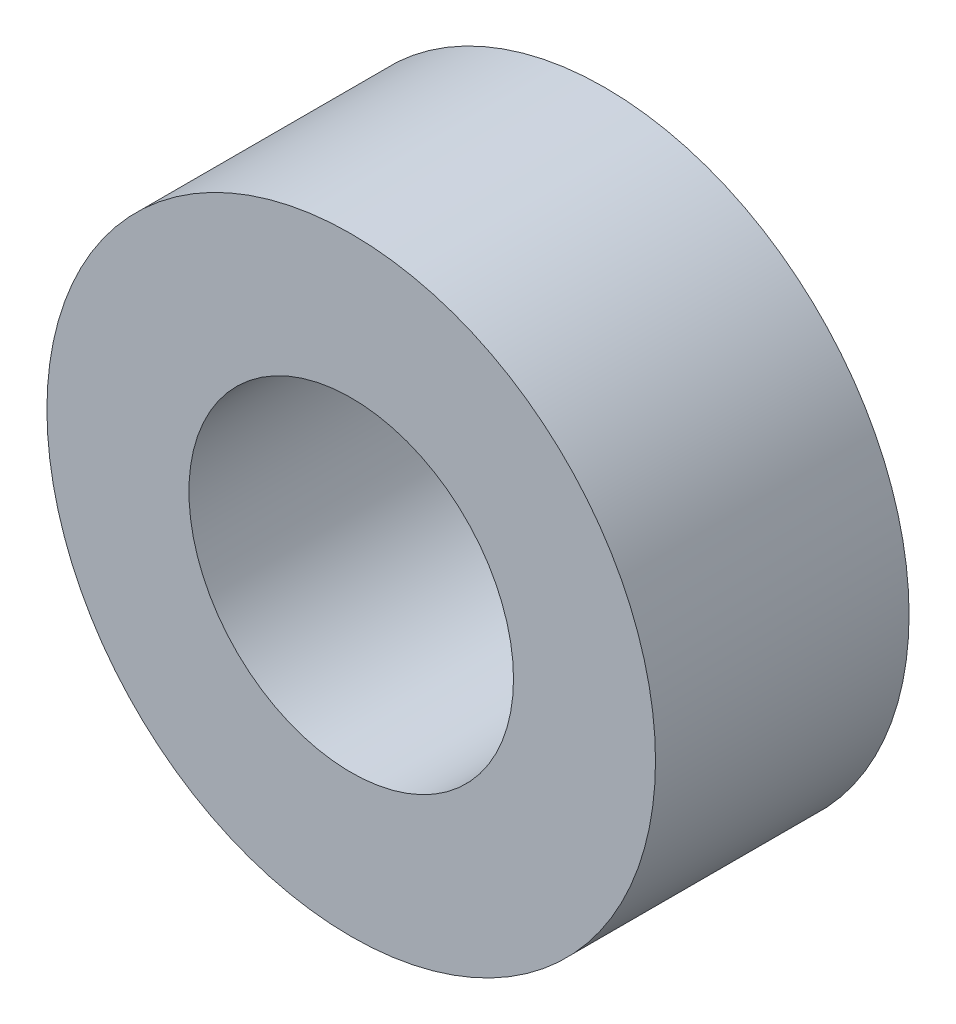
SolidWorks part; units mm, degrees
material "6063-T5"
ref_plane "正面" through (0, 0, 0) normal (0, 0, 1) x (1, 0, 0)
ref_plane "平面" through (0, 0, 0) normal (0, 1, 0) x (1, 0, 0)
ref_plane "右側面" through (0, 0, 0) normal (1, 0, 0) x (0, 0, -1)
sketch "ｽｹｯﾁ1" plane through (0, 0, 0) normal (0, 0, 1) x (1, 0, 0)
  circle A0 centre (0, 0) radius 1.6
  circle A1 centre (0, 0) radius 3
  dimension "D1" = 6
  dimension "D2" = 3.2
extrude "ﾎﾞｽ - 押し出し1" add sketch "ｽｹｯﾁ1" along normal blind 2.5
